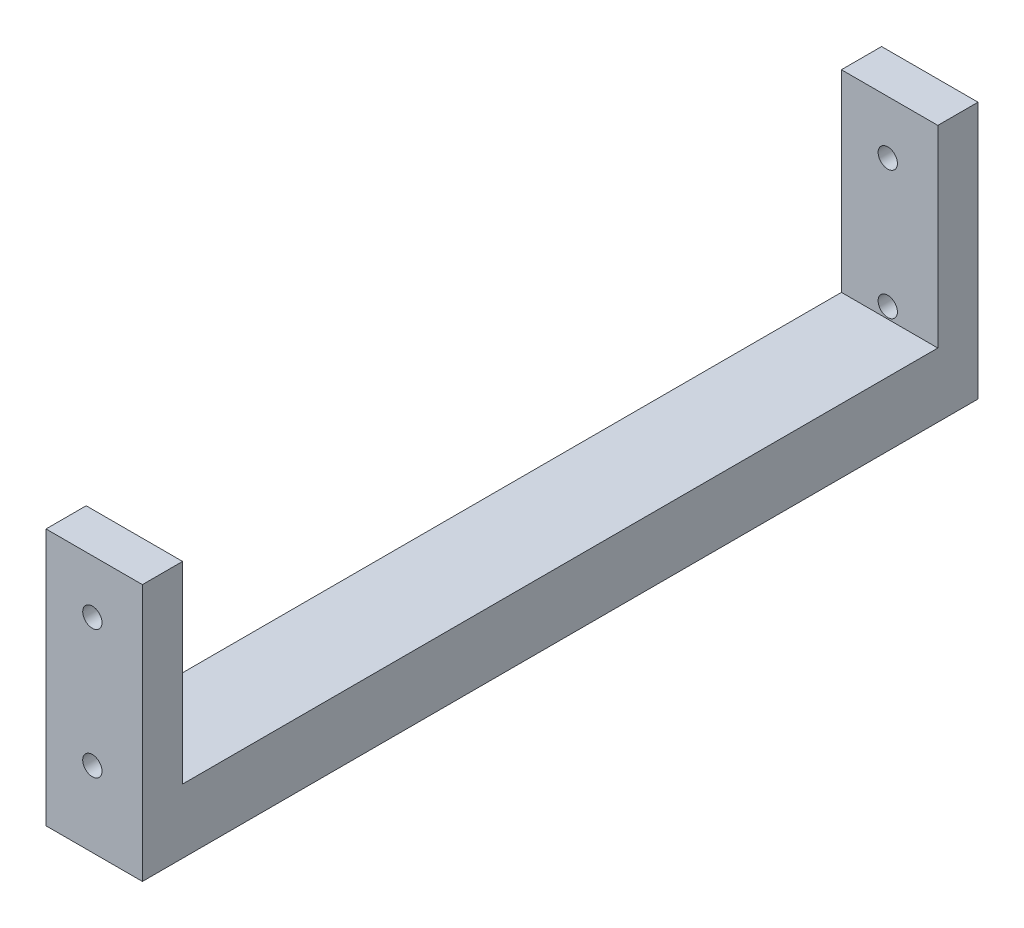
SolidWorks part; units mm, degrees
ref_plane "Front Plane" through (0, 0, 0) normal (0, 0, 1) x (1, 0, 0)
ref_plane "Top Plane" through (0, 0, 0) normal (0, 1, 0) x (1, 0, 0)
ref_plane "Right Plane" through (0, 0, 0) normal (1, 0, 0) x (0, 0, -1)
sketch "Sketch1" plane through (0, 0, 0) normal (0, 0, 1) x (1, 0, 0)
  line L1 (-7.5, 25) -> (7.5, 25)
  line L2 (-7.5, 25) -> (-7.5, -15)
  line L3 (-7.5, -15) -> (7.5, -15)
  line L4 (7.5, 25) -> (7.5, -15)
  dimension "D1" = 15
  dimension "D2" = 40
  dimension "D3" = 7.5
  dimension "D4" = 15
extrude "Boss-Extrude1" add sketch "Sketch1" along normal blind 130
sketch "Sketch2" plane through (0, 25, 0) normal (0, 1, 0) x (1, 0, 0)
  line L0 (-7.5, -130) -> (-7.5, 0) construction
  line L1 (-7.5, -6.25) -> (7.5, -6.25)
  line L2 (-7.5, -6.25) -> (-7.5, -123.75)
  line L3 (-7.5, -123.75) -> (7.5, -123.75)
  line L4 (7.5, -6.25) -> (7.5, -123.75)
  line L5 (7.5, -130) -> (7.5, 0) construction
  line L6 (7.5, -130) -> (-7.5, -130) construction
  dimension "1" = 117.5
  dimension "6.25" = 6.25
extrude "Cut-Extrude1" cut sketch "Sketch2" against normal blind 30
sketch "Sketch3" plane through (0, 0, 0) normal (0, 0, -1) x (-1, 0, 0)
  circle A0 centre (0.2894, 16.7166) radius 1.5
  circle A1 centre (0.2894, -3.2834) radius 1.5
  dimension "D2" = 3
  dimension "D3" = 3
  dimension "D1" = 20
extrude "Cut-Extrude2" cut sketch "Sketch3" against normal through all both and the other way through all
